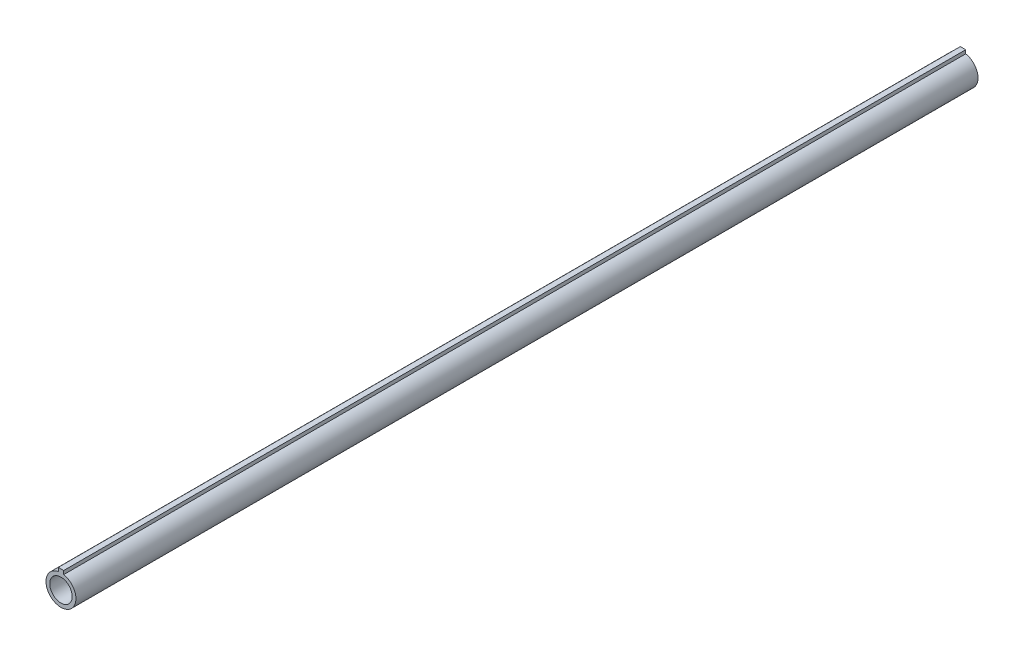
SolidWorks part; units mm, degrees
ref_plane "Alzado" through (0, 0, 0) normal (0, 0, 1) x (1, 0, 0)
ref_plane "Planta" through (0, 0, 0) normal (0, 1, 0) x (1, 0, 0)
ref_plane "Vista lateral" through (0, 0, 0) normal (1, 0, 0) x (0, 0, -1)
sketch "Croquis1" plane through (0, 0, 0) normal (0, 0, 1) x (1, 0, 0)
  line L0 (-77.6276, 118.8395) -> (-77.6276, 121.3395) construction
  line L3 (-78.0776, 121.2987) -> (-78.0776, 121.8987)
  line L4 (-78.0776, 121.8987) -> (-77.1776, 121.8987)
  line L5 (-77.1776, 121.2987) -> (-77.1776, 121.8987)
  arc A0 (-78.0776, 121.2987) -> (-77.1776, 121.2987) centre (-77.6276, 118.8395) ccw
  dimension "D1" = 5
  dimension "D2" = 0.9
  dimension "D3" = 0.6
extrude "Saliente-Extruir1" add sketch "Croquis1" along normal blind 150.6
sketch "Croquis2" plane through (0, 0, 150.6) normal (0, 0, 1) x (1, 0, 0)
  circle A0 centre (-77.6276, 118.8395) radius 1.875
  dimension "D1" = 3.75
extrude "Cortar-Extruir1" cut sketch "Croquis2" against normal blind 72
sketch "Croquis3" plane through (0, 0, 0) normal (0, 0, -1) x (-1, 0, 0)
  circle A0 centre (77.6276, 118.8395) radius 1.875
  dimension "D1" = 3.75
extrude "Cortar-Extruir2" cut sketch "Croquis3" against normal blind 72
